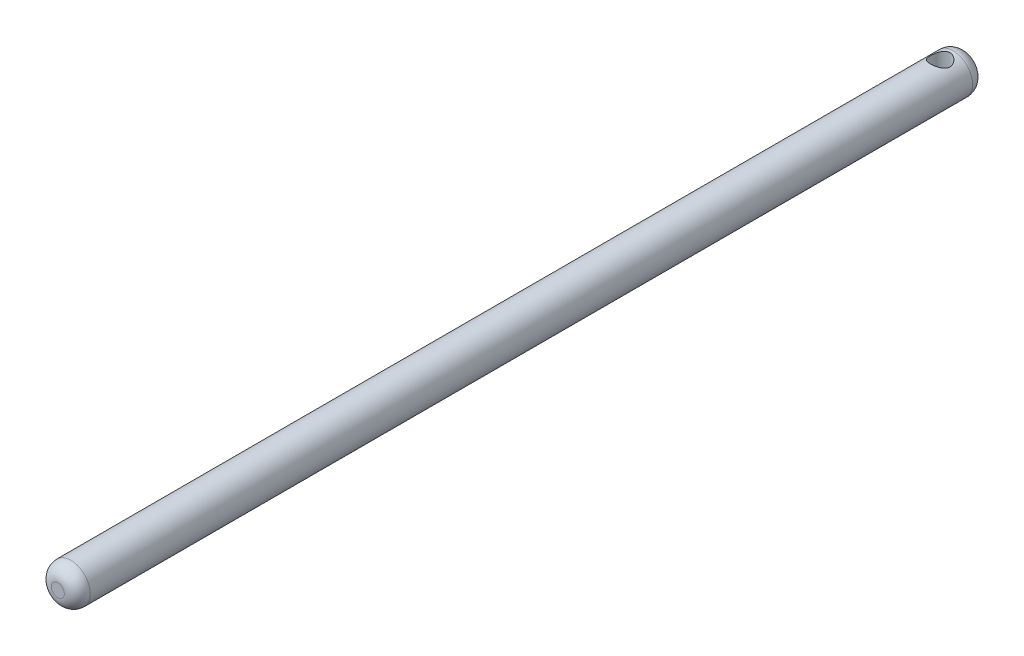
SolidWorks part; units mm, degrees
ref_plane "Front Plane" through (0, 0, 0) normal (0, 0, 1) x (1, 0, 0)
ref_plane "Top Plane" through (0, 0, 0) normal (0, 1, 0) x (1, 0, 0)
ref_plane "Right Plane" through (0, 0, 0) normal (1, 0, 0) x (0, 0, -1)
sketch "Sketch1" plane through (0, 0, 0) normal (0, 0, 1) x (1, 0, 0)
  circle A0 centre (0, 0) radius 2.3812
  point P4 (-2.3812, 0)
  dimension "Diameter" = 4.7625
sketch "Sketch2" plane through (0, 0, 0) normal (1, 0, 0) x (0, 0, -1)
  line L0 (-55.5625, 0) -> (55.5625, 0)
  line L1 (0, -2.3812) -> (0, 2.3812) construction
  line L2 (0, 2.3812) -> (0, -2.3812) construction
  line L3 (55.5625, -2.3813) -> (55.5625, 2.3812)
  line L4 (-55.5625, -2.3812) -> (-55.5625, 2.3812)
  point P0 (30.1625, 0)
  point P4 (0, 0)
  point P6 (-30.1625, 0)
  point P12 (0, 0)
  point P15 (55.5625, 0)
  point P18 (-55.5625, 0)
  dimension "D1" = 25.4
  dimension "Length" = 111.125
sketch "Sketch3" plane through (0, 0, 0) normal (0, 0, 1) x (1, 0, 0)
  circle A1 centre (0, 0) radius 2.3812
  circle A5 centre (0, 0) radius 2.3812
  dimension "D1" = 0
extrude "Boss-Extrude1" add sketch "Sketch3" along normal mid plane 111.125
fillet "Fillet2" radius 1.5875 1 edges at (2.3812, 0, 55.5625)
ref_plane "Plane1" through (0, 2.3813, 0) normal (0, 1, 0) x (1, 0, 0)
sketch "Sketch4" plane through (0, 2.3813, 0) normal (0, 1, 0) x (1, 0, 0)
  line L0 (0, 55.5625) -> (0, 52.3875) construction
  line L1 (2.3812, 55.5625) -> (-2.3812, 55.5625) construction
hole_wizard "3/32 (0.09375) Diameter Hole3" positions "Sketch10" profile "Sketch11" hole size "3/32" standard "ANSI Inch" end condition through all
sketch "Sketch10" plane through (0, 2.3813, 0) normal (0, 1, 0) x (1, 0, 0)
  point P0 (0, 52.3875)
sketch "Sketch11" plane through (0, 2.3813, -52.3875) normal (1, 0, 0) x (0, 0, 1)
  line L0 (0, 0) -> (0, 4.7625)
  line L1 (0, 4.7625) -> (1.1906, 4.7625)
  line L2 (1.1906, 4.7625) -> (1.1906, 0)
  line L5 (1.1906, 0) -> (0, 0)
  line L11 (0, -6.35) -> (0, 107.95) construction
  dimension "Thru Hole Dia." = 2.3812
  dimension "Thru Hole Depth" = 4.7625
fillet "Fillet3" radius 1.5875 1 edges at (2.3812, 0, -55.5625)
equation "\"D1@Boss-Extrude1\"=\"Length@Sketch2\""
